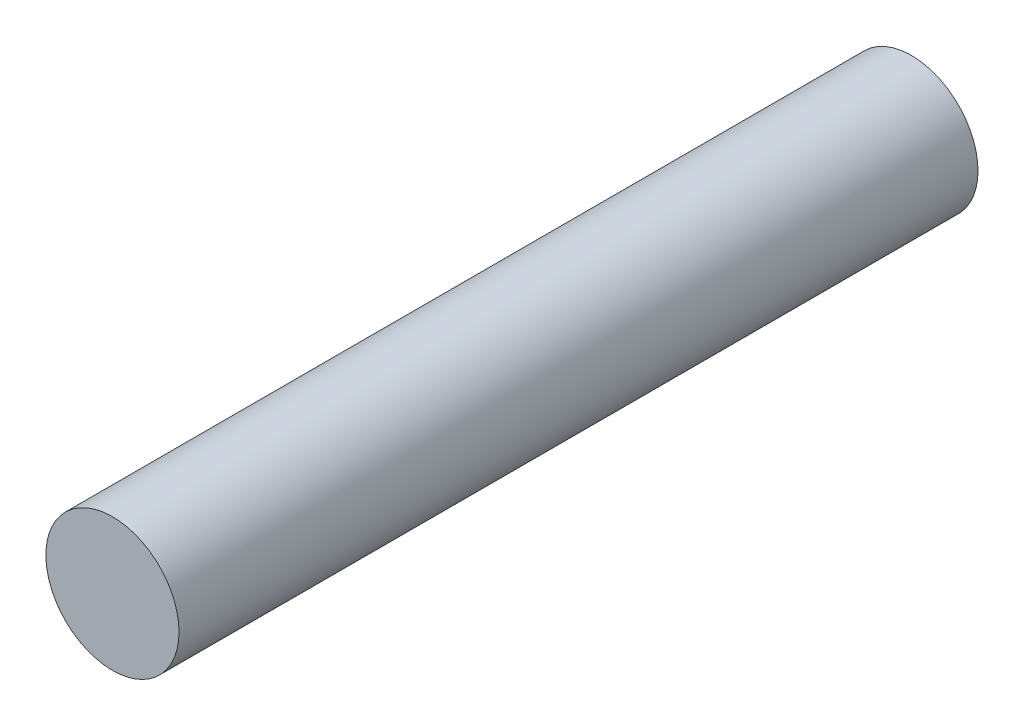
SolidWorks part; units mm, degrees
ref_plane "Front Plane" through (0, 0, 0) normal (0, 0, 1) x (1, 0, 0)
ref_plane "Top Plane" through (0, 0, 0) normal (0, 1, 0) x (1, 0, 0)
ref_plane "Right Plane" through (0, 0, 0) normal (1, 0, 0) x (0, 0, -1)
sketch "Sketch1" plane through (0, 0, 0) normal (0, 0, 1) x (1, 0, 0)
  circle A0 centre (0, 0) radius 5
  dimension "D1" = 10
extrude "Boss-Extrude1" add sketch "Sketch1" along normal blind 60
sketch "Sketch2" plane through (0, 0, 0) normal (0, 0, -1) x (-1, 0, 0)
  line L3 (-2.5, -2) -> (2.5, -2)
  line L4 (-2.5, -2) -> (-2.5, 2)
  line L5 (-2.5, 2) -> (2.5, 2)
  line L6 (2.5, -2) -> (2.5, 2)
  line L7 (-2.5, -2) -> (2.5, 2) construction
  line L8 (-2.5, 2) -> (2.5, -2) construction
  point P5 (0, 0)
  dimension "D1" = 4
  dimension "D2" = 5
extrude "Cut-Extrude1" cut sketch "Sketch2" against normal blind 40
sketch "Sketch4" plane through (0, 0, 0) normal (1, 0, 0) x (0, 0, -1)
  circle A0 centre (-52, 0) radius 2
  dimension "D3" = 4
extrude "Cut-Extrude2" cut sketch "Sketch4" against normal blind 40
